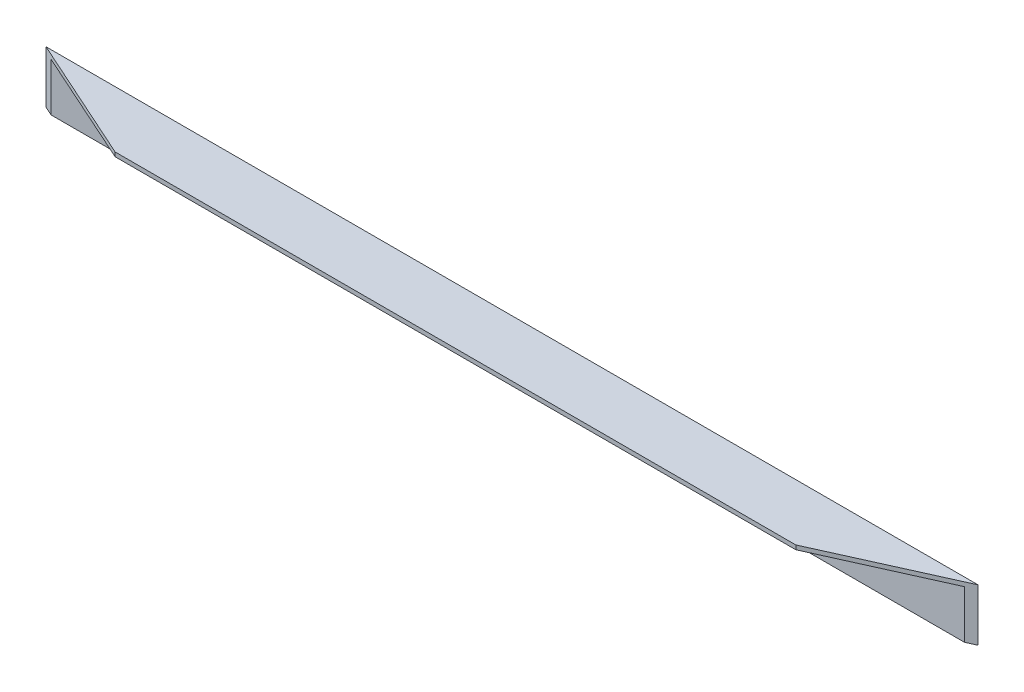
SolidWorks part; units mm, degrees
ref_plane "前视" through (0, 0, 0) normal (0, 0, 1) x (1, 0, 0)
ref_plane "上视" through (0, 0, 0) normal (0, 1, 0) x (1, 0, 0)
ref_plane "右视" through (0, 0, 0) normal (1, 0, 0) x (0, 0, -1)
sketch "草图1" plane through (0, 0, 0) normal (0, 0, 1) x (1, 0, 0)
  line L0 (0, 0) -> (0, 72.6209) construction
  line L1 (-890, 0) -> (890, 0)
  line L2 (-890, 0) -> (-890, 100)
  line L3 (-890, 100) -> (890, 100)
  line L4 (890, 0) -> (890, 100)
  line L5 (1568.3745, 40) -> (1028.9756, 40) construction
  line L6 (1022.2249, 40) -> (468.717, 40) construction
  line L7 (468.717, 40) -> (338.4799, 40) construction
  line L8 (346.077, 40) -> (224.5223, 40) construction
  line L9 (0, 72.6209) -> (0, 232.7989) construction
  line L10 (1000, 433.3131) -> (1000, -1026.6948) construction
  line L11 (-1000, 516.3236) -> (-1000, -1344.0878) construction
  dimension "D1" = 1780
  dimension "D2" = 100
  dimension "D3" = 40
extrude "基体-拉伸" add sketch "草图1" along normal blind 8
sketch "草图2" plane through (0, 0, 8) normal (0, 0, 1) x (1, 0, 0)
  line L0 (890, 0) -> (890, 100) construction
  line L1 (-890, 100) -> (890, 100)
  line L2 (-890, 100) -> (-890, 92)
  line L3 (-890, 92) -> (890, 92)
  line L4 (890, 100) -> (890, 92)
  dimension "D1" = 8
extrude "凸台-拉伸1" add sketch "草图2" along normal blind 100
sketch "草图3" plane through (0, 100, 0) normal (0, 1, 0) x (-1, 0, 0)
  line L0 (-890, 108) -> (890, 108) construction
  line L1 (-650, 108) -> (-890, 0)
  line L2 (-890, 0) -> (-890, 108)
  line L3 (-890, 108) -> (-650, 108)
  line L4 (0, -34.4051) -> (0, 171.3565) construction
  line L5 (890, 108) -> (650, 108)
  line L6 (890, 0) -> (890, 108)
  line L7 (650, 108) -> (890, 0)
  point P0 (-650, 108)
  dimension "D1" = 240
extrude "切除-拉伸1" cut sketch "草图3" against normal through all
